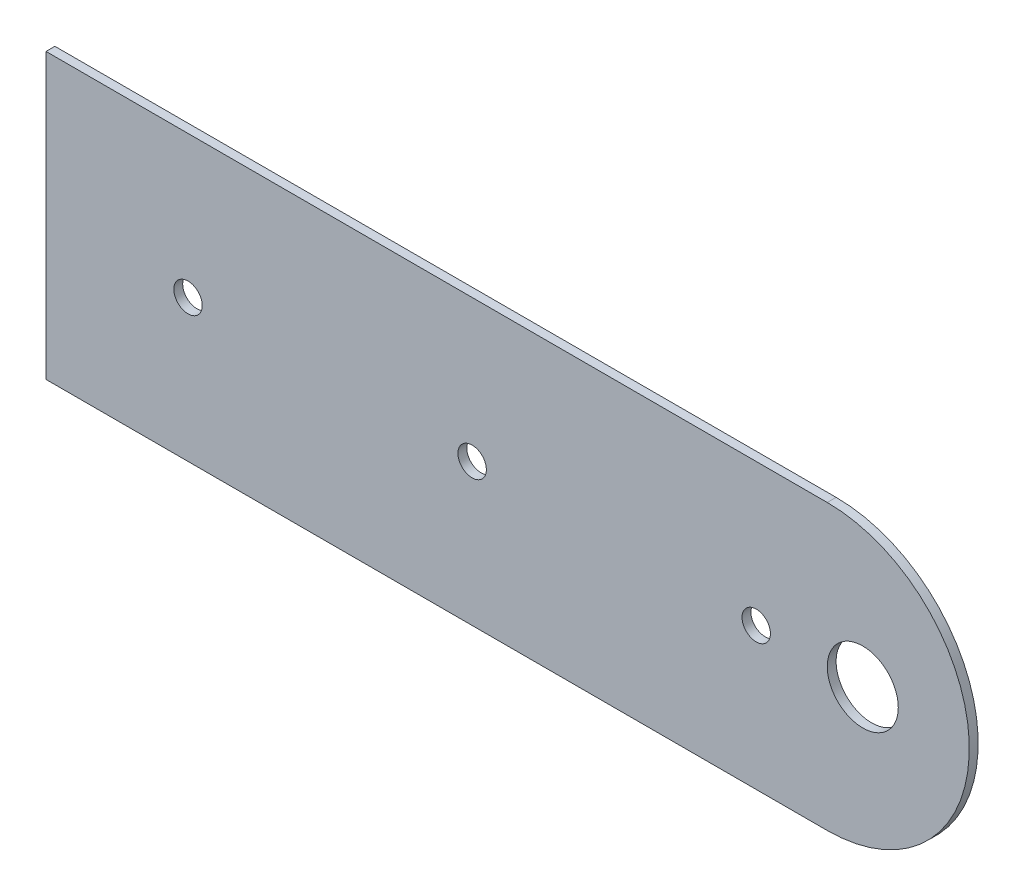
SolidWorks part; units mm, degrees
material "1060 Alloy"
ref_plane "Front Plane" through (0, 0, 0) normal (0, 0, 1) x (1, 0, 0)
ref_plane "Top Plane" through (0, 0, 0) normal (0, 1, 0) x (1, 0, 0)
ref_plane "Right Plane" through (0, 0, 0) normal (1, 0, 0) x (0, 0, -1)
sketch "Sketch1" plane through (0, 0, 0) normal (0, 0, 1) x (1, 0, 0)
  line L1 (0, 0) -> (139.7, 0)
  line L2 (0, 0) -> (0, 50.8)
  line L3 (0, 50.8) -> (139.7, 50.8)
  arc A1 (139.7, 50.8) -> (139.7, 0) centre (139.7, 25.4) cw
  circle A3 centre (146.05, 25.4) radius 6.35
  circle A4 centre (25.4, 25.4) radius 2.54
  circle A5 centre (76.2, 25.4) radius 2.54
  circle A6 centre (127, 25.4) radius 2.54
  point P7 (127, 50.8)
  dimension "D3" = 6.35
  dimension "D4" = 12.7
  dimension "D5" = 5.08
  dimension "D1" = 139.7
  dimension "D2" = 50.8
  dimension "D6" = 25.4
  dimension "D7" = 50.8
  dimension "D8" = 50.8
extrude "Boss-Extrude1" add sketch "Sketch1" along normal blind 1.5875
